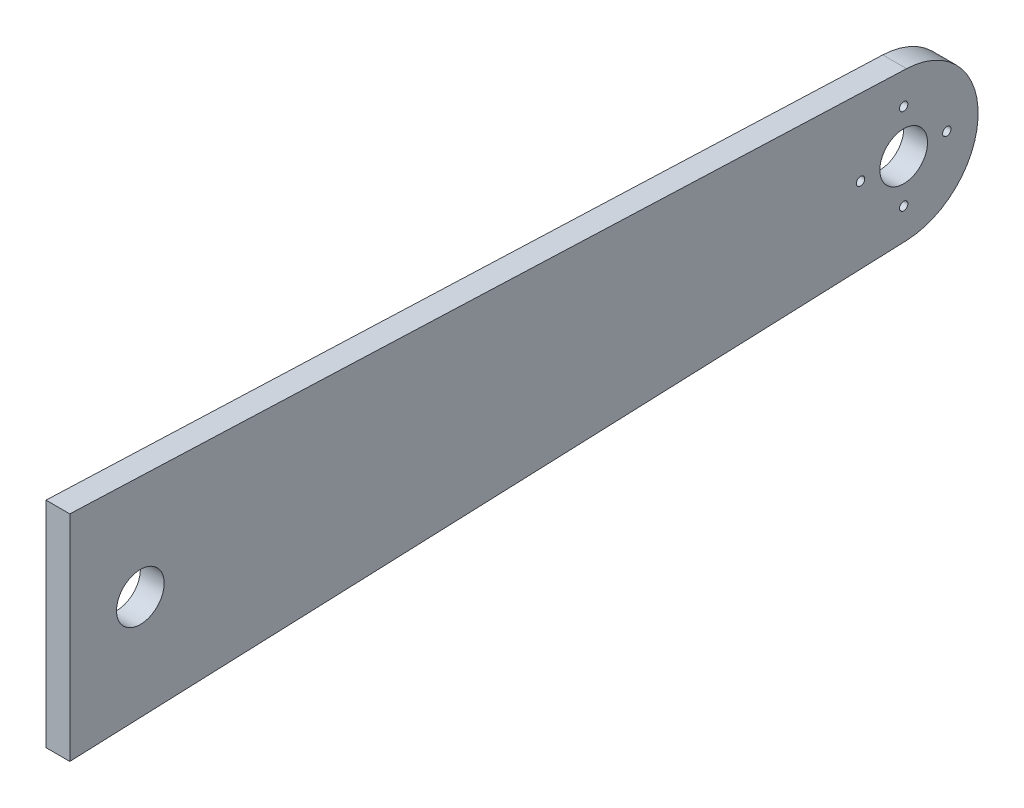
SolidWorks part; units mm, degrees
ref_plane "Front Plane" through (0, 0, 0) normal (0, 0, 1) x (1, 0, 0)
ref_plane "Top Plane" through (0, 0, 0) normal (0, 1, 0) x (1, 0, 0)
ref_plane "Right Plane" through (0, 0, 0) normal (1, 0, 0) x (0, 0, -1)
sketch "Sketch1" plane through (0, 0, 0) normal (1, 0, 0) x (0, 0, -1)
  line L0 (-140, 18) -> (-140, -18)
  line L19 (-140, 18) -> (0.4898, 12.4904)
  line L20 (-140, -18) -> (0.4898, -12.4904)
  circle A0 centre (0, 0) radius 4
  circle A1 centre (-7.24, 0) radius 0.7
  circle A2 centre (0, 7.24) radius 0.7
  circle A3 centre (7.24, 0) radius 0.7
  circle A4 centre (0, -7.24) radius 0.7
  arc A5 (0.4898, -12.4904) -> (0.4898, 12.4904) centre (0, 0) ccw
  point P18 (0, 0)
  dimension "D1" = 8
  dimension "D2" = 1.4
  dimension "D5" = 140
  dimension "D9" = 25
  dimension "D3" = 7.24
  dimension "D6" = 4.492
  dimension "D7" = 87.754
  dimension "D4" = 4
extrude "Boss-Extrude1" add sketch "Sketch1" along normal blind 4
sketch "Sketch2" plane through (4, 0, 0) normal (1, 0, 0) x (0, 0, -1)
  line L0 (0, 0) -> (-140, 0) construction
  line L1 (-140, 18) -> (-140, -18) construction
  circle A0 centre (-128.1588, 0) radius 4
  dimension "D1" = 8
extrude "Cut-Extrude1" cut sketch "Sketch2" against normal blind 10
